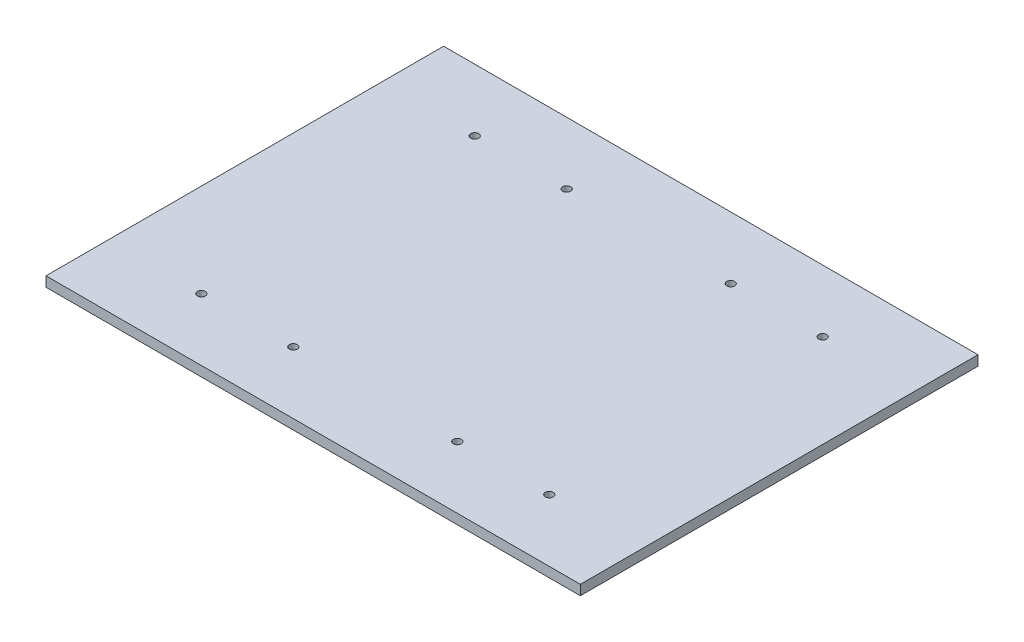
SolidWorks part; units mm, degrees
ref_plane "Front Plane" through (0, 0, 0) normal (0, 0, 1) x (1, 0, 0)
ref_plane "Top Plane" through (0, 0, 0) normal (0, 1, 0) x (1, 0, 0)
ref_plane "Right Plane" through (0, 0, 0) normal (1, 0, 0) x (0, 0, -1)
sketch "Sketch1" plane through (0, 0, 0) normal (0, 1, 0) x (1, 0, 0)
  line L1 (-107.5, 80) -> (107.5, 80)
  line L2 (-107.5, 80) -> (-107.5, -80)
  line L3 (-107.5, -80) -> (107.5, -80)
  line L4 (107.5, 80) -> (107.5, -80)
  line L5 (-107.5, 80) -> (107.5, -80) construction
  line L6 (-107.5, -80) -> (107.5, 80) construction
  point P0 (0, 0)
  dimension "D1" = 160
  dimension "D2" = 215
extrude "Boss-Extrude1" add sketch "Sketch1" along normal blind 4 contours L2 L1 L4 L3
sketch "Sketch3" plane through (0, 0, 0) normal (0, -1, 0) x (1, 0, 0)
  line L0 (-107.5, -80) -> (-107.5, 80) construction
  line L1 (-107.5, 80) -> (107.5, 80) construction
  line L2 (107.5, -80) -> (107.5, 80) construction
  line L6 (-107.5, 0) -> (107.5, 0) construction
  line L7 (0, 80) -> (0, -80) construction
  line L8 (-107.5, -80) -> (107.5, -80) construction
  circle A0 centre (-70, 55) radius 10.2331
  circle A4 centre (33, 55) radius 10.2331
  circle A5 centre (-33, 55) radius 10.2331
  circle A6 centre (70, 55) radius 10.2331
  circle A7 centre (70, -55) radius 10.2331
  circle A8 centre (33, -55) radius 10.2331
  circle A9 centre (-33, -55) radius 10.2331
  circle A10 centre (-70, -55) radius 10.2331
  point P0 (-70, 55)
  point P6 (33, 55)
  point P12 (-33, 55)
  point P14 (70, 55)
  point P16 (70, -55)
  point P22 (33, -55)
  point P24 (-33, -55)
  point P26 (-70, -55)
  dimension "D1" = 55
  dimension "D3" = 33
  dimension "D5" = 55
  dimension "D7" = 70
  dimension "D2" = 70
  dimension "D4" = 55
  dimension "D6" = 33
hole_wizard "Ø1.0 (3.2) Diameter Hole1" positions "Sketch3" profile "Sketch6" hole size "Ø1.0" standard "ANSI Metric" end condition through all
sketch "Sketch6" plane through (-70, 0, 55) normal (1, 0, 0) x (0, 0, -1)
  line L0 (0, 0) -> (0, 4)
  line L1 (0, 4) -> (1.6, 4)
  line L2 (1.6, 4) -> (1.6, 0)
  line L5 (1.6, 0) -> (0, 0)
  line L11 (0, -6.35) -> (0, 107.95) construction
  dimension "Thru Hole Dia." = 3.2
  dimension "Thru Hole Depth" = 4
